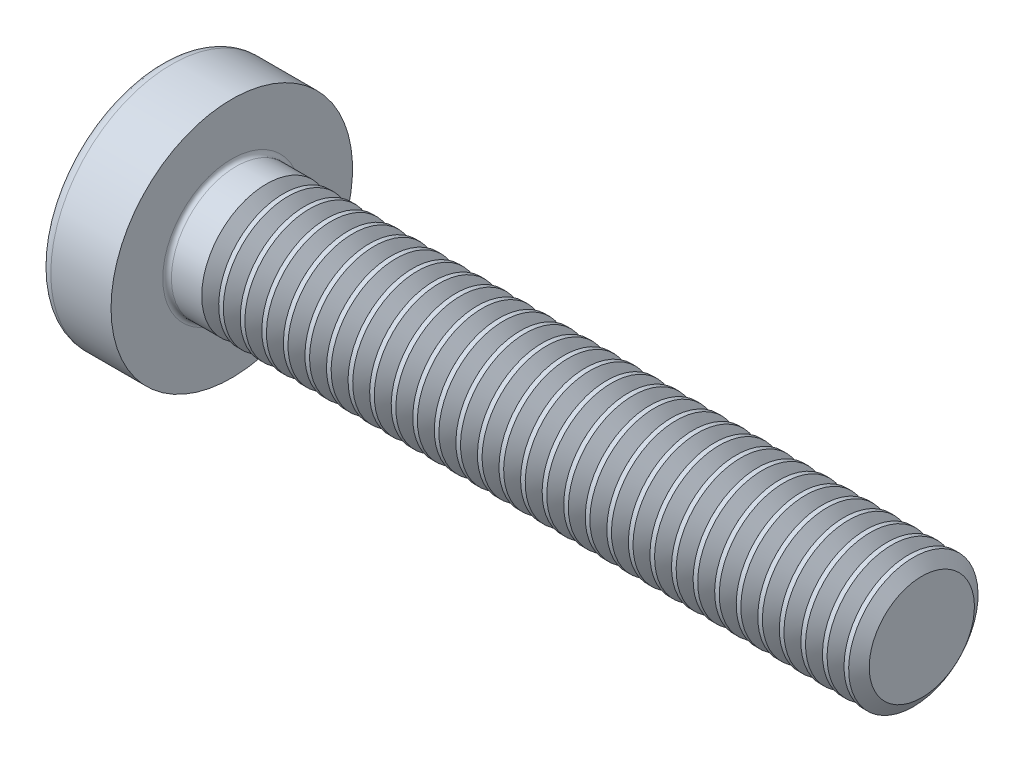
SolidWorks part; units mm, degrees
ref_plane "Plane1" through (0, 0, 0) normal (0, 0, 1) x (1, 0, 0)
ref_plane "Plane2" through (0, 0, 0) normal (0, 1, 0) x (1, 0, 0)
ref_plane "Plane3" through (0, 0, 0) normal (1, 0, 0) x (0, 0, -1)
sketch "BodySke" plane through (0, 0, 0) normal (0, 0, 1) x (1, 0, 0)
  line L0 (2.4, 1.5) -> (2.4, 2.8)
  line L1 (2.65, 6.35) -> (2.65, -3.175) construction
  line L2 (-25.4, 0) -> (127, 0) construction
  line L3 (18.4, 0) -> (0, 0)
  line L4 (2.4, 1.5) -> (18.4, 1.5)
  line L5 (18.4, 1.5) -> (18.4, 0)
  line L6 (1.0035, 2.8) -> (2.4, 2.8)
  line L8 (2.4, 6.35) -> (2.4, -3.175) construction
  arc A0 (0.7754, 2.6744) -> (0, 0) centre (5, 0) ccw
  arc A2 (0.7754, 2.6744) -> (1.0035, 2.8) centre (1.0035, 2.53) cw
  dimension "Head_crown_rad" = 5
  dimension "Head_fillet_rad" = 0.27
  dimension "Length" = 16
  dimension "Head_ht" = 2.4
  dimension "Head_dia" = 5.6
  dimension "Advance" = 0.5
  dimension "Thread_nom" = 16
  dimension "Diameter" = 3
revolve "Base-Revolve" add sketch "BodySke"
cosmetic thread "ThreadCosmetic" [suppressed]
fillet "Fillet1" radius 0.1 1 edges at (2.4, 0, 1.5)
sketch "Sketch3" plane through (0, 0, 0) normal (1, 0, 0) x (0, 0, -1)
  line L0 (0.37, -1.4) -> (-0.37, -1.4)
  line L1 (0.37, -1.4) -> (0.37, 1.4)
  line L2 (-0.37, 1.4) -> (0.37, 1.4)
  line L3 (-0.37, 1.4) -> (-0.37, -1.4)
  dimension "Cross_dia" = 2.8
  dimension "D1" = 1.4
  dimension "Cross_width" = 0.74
  dimension "D2" = 0.37
ref_plane "Plane4" through (1.75, 0, 0) normal (1, 0, 0) x (0, 0, -1)
sketch "Sketch4" plane through (1.75, 0, 0) normal (1, 0, 0) x (0, 0, -1)
  line L0 (0.37, -0.5275) -> (-0.37, -0.5275)
  line L1 (0.37, -0.5275) -> (0.37, 0.5275)
  line L2 (-0.37, 0.5275) -> (0.37, 0.5275)
  line L3 (-0.37, 0.5275) -> (-0.37, -0.5275)
  dimension "D1" = 0.74
  dimension "D2" = 1.055
  dimension "D3" = 0.37
  dimension "D4" = 0.5275
loft "Recess" cut profiles "Sketch3", "Sketch4"
pattern_circular "RecPat" count 2 every 90 about axis through (0, 0, 0) along (1, 0, 0) of "Recess"
sketch "RecCorSke" plane through (0, 0, 0) normal (0, 0, 1) x (1, 0, 0)
  line L0 (-3.175, 0) -> (15.875, 0) construction
  line L1 (-25.4, 0) -> (127, 0) construction
  line L2 (0, 0) -> (0, 0.6784)
  line L3 (0, 0.6784) -> (1.75, 0.556)
  line L4 (1.75, 0.556) -> (1.9307, 0)
  line L5 (1.9307, 0) -> (0, 0)
  dimension "Diameter" = 1.112
  dimension "Depth" = 1.75
  dimension "Draft_angle" = 4
  dimension "Bottom_angle" = 18
revolve "RecessCore" cut sketch "RecCorSke" angle 360 about L0
sketch "ThdSchSke" plane through (0, 0, 0) normal (0, 0, 1) x (1, 0, 0)
  line L0 (3.4, -1.2195) -> (3.2036, -1.5)
  line L1 (3.4, -1.2195) -> (3.5964, -1.5)
  line L2 (3.5964, -1.5) -> (3.5964, -1.875)
  line L3 (-3.175, 0) -> (5.1513, 0) construction
  line L5 (3.5964, -1.875) -> (3.2036, -1.875)
  line L6 (3.2036, -1.875) -> (3.2036, -1.5)
  dimension "Diameter" = 3
  dimension "SideAngle" = 55
  dimension "VeeAngle" = 70
  dimension "Thread_minor" = 2.439
  dimension "Overcut" = 3.75
  dimension "Start" = 3.4
revolve "ThreadSchematic" cut sketch "ThdSchSke" angle 360 about L3
pattern_linear "ThdSchPat" count 31 spacing 0.5 along (1, 0, 0) of "ThreadSchematic"
equation "\"D1@Sketch3\" = \"Cross_dia@Sketch3\" / 2"
equation "\"D2@Sketch3\" = \"Cross_width@Sketch3\" / 2"
equation "\"Depth@RecCorSke\" = \"Cross_depth@Plane4\""
equation "\"D1@Sketch4\" = \"Cross_width@Sketch3\""
equation "\"D2@Sketch4\" = \"Cross_dia@Sketch3\" - 2.0 * \"Cross_depth@Plane4\" * tan(26.5  * 0.017453292)"
equation "\"D3@Sketch4\" = \"D1@Sketch4\" / 2"
equation "\"D4@Sketch4\" = \"D2@Sketch4\" / 2"
equation "\"Thread_length@ThreadCosmetic\" = ((sgn( (\"Length@BodySke\" - \"Advance@BodySke\" * 2.0 ) - \"Thread_nom@BodySke\" )-1)*( (\"Length@BodySke\" - \"Advance@BodySke\" * 2.0 ) - \"Thread_nom@BodySke\" ))/-2+ \"Thread_nom@BodySke\""
equation "\"Thread_minor@ThdSchSke\" = \"Thread_minor@ThreadCosmetic\""
equation "\"Diameter@ThdSchSke\" = \"Diameter@BodySke\""
equation "\"Overcut@ThdSchSke\" = \"Diameter@BodySke\" * 1.25"
equation "\"Start@ThdSchSke\" = \"Head_ht@BodySke\" + \"Length@BodySke\" - \"Thread_length@ThreadCosmetic\"  '---Non-countersunk---"
equation "\"Num_threads@ThdSchPat\" = int( \"Thread_length@ThreadCosmetic\" / \"Advance@BodySke\" + 0.999 )  + 1"
equation "\"Advance@ThdSchPat\" = \"Thread_length@ThreadCosmetic\" /  (\"Num_threads@ThdSchPat\" - 1) 'relax it"
